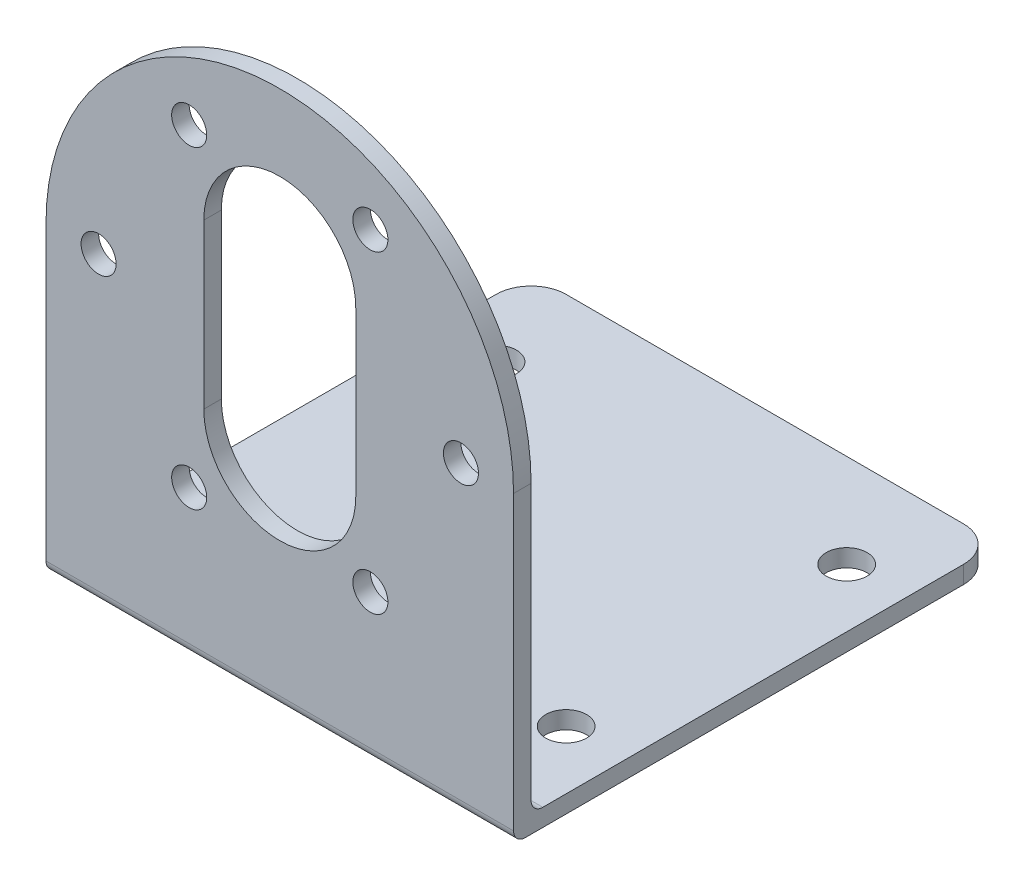
SolidWorks part; units mm, degrees
ref_plane "前视基准面" through (0, 0, 0) normal (0, 0, 1) x (1, 0, 0)
ref_plane "上视基准面" through (0, 0, 0) normal (0, 1, 0) x (1, 0, 0)
ref_plane "右视基准面" through (0, 0, 0) normal (1, 0, 0) x (0, 0, -1)
sketch "草图1" plane through (0, 0, 0) normal (0, 0, 1) x (1, 0, 0)
  line L1 (7.75, -13.4234) -> (15.5, 0) construction
  line L2 (15.5, 0) -> (7.75, 13.4234) construction
  line L3 (7.75, 13.4234) -> (-7.75, 13.4234) construction
  line L4 (-7.75, 13.4234) -> (-15.5, 0) construction
  line L5 (-15.5, 0) -> (-7.75, -13.4234) construction
  line L6 (-7.75, -13.4234) -> (7.75, -13.4234) construction
  line L8 (-20, 0) -> (-20, -26)
  line L9 (-20, -26) -> (20, -26)
  line L10 (20, 0) -> (20, -26)
  line L13 (-6.5, 7) -> (-6.5, -7)
  line L15 (6.5, 7) -> (6.5, -7)
  line L16 (-6.5, 7) -> (6.5, -7) construction
  line L17 (-6.5, -7) -> (6.5, 7) construction
  arc A0 (20, 0) -> (-20, 0) centre (0, 0) ccw
  circle A1 centre (0, 0) radius 15.5 construction
  circle A2 centre (-7.75, 13.4234) radius 1.5
  circle A3 centre (7.75, 13.4234) radius 1.5
  circle A4 centre (15.5, 0) radius 1.5
  circle A5 centre (7.75, -13.4234) radius 1.5
  circle A6 centre (-7.75, -13.4234) radius 1.5
  circle A7 centre (-15.5, 0) radius 1.5
  arc A8 (-6.5, 7) -> (6.5, 7) centre (0, 7) cw
  arc A9 (-6.5, -7) -> (6.5, -7) centre (0, -7) ccw
  point P23 (0.2419, 0.419)
  point P34 (0, 0)
  dimension "D1" = 6
  dimension "D3" = 40
  dimension "D4" = 31
  dimension "D6" = 3
  dimension "D2" = 26
  dimension "D5" = 40
  dimension "D7" = 14
  dimension "D8" = 13
extrude "凸台-拉伸1" add sketch "草图1" along normal blind 1.5
sketch "草图2" plane through (0, 0, 0) normal (0, 0, -1) x (-1, 0, 0)
  line L2 (-20, -26) -> (20, -26)
  line L3 (-20, -26) -> (-20, -24.5)
  line L4 (-20, -24.5) -> (20, -24.5)
  line L5 (20, -26) -> (20, -24.5)
  dimension "D1" = 1.5
  dimension "D2" = 40
extrude "凸台-拉伸2" add sketch "草图2" along normal blind 40
sketch "草图3" plane through (0, -24.5, 0) normal (0, 1, 0) x (1, 0, 0)
  line L0 (0, 40) -> (0, 0) construction
  line L1 (-20, 40) -> (20, 40) construction
  line L3 (-15, 32) -> (15, 32) construction
  line L4 (-15, 32) -> (-15, 8) construction
  line L5 (-15, 8) -> (15, 8) construction
  line L6 (15, 32) -> (15, 8) construction
  line L7 (-15, 32) -> (15, 8) construction
  line L8 (-15, 8) -> (15, 32) construction
  circle A0 centre (-15, 32) radius 1.75
  circle A1 centre (-15, 8) radius 1.75
  circle A2 centre (15, 8) radius 1.75
  circle A3 centre (15, 32) radius 1.75
  point P5 (0, 20)
  dimension "D3" = 3.5
  dimension "D4" = 3.5
  dimension "D1" = 30
  dimension "D2" = 24
extrude "切除-拉伸1" cut sketch "草图3" against normal blind 40
fillet "圆角1" radius 3 2 edges at (20, -25.25, -40) (-20, -25.25, -40)
fillet "圆角2" radius 1 2 edges at (0, -26, 1.5) (0, -24.5, 0)
